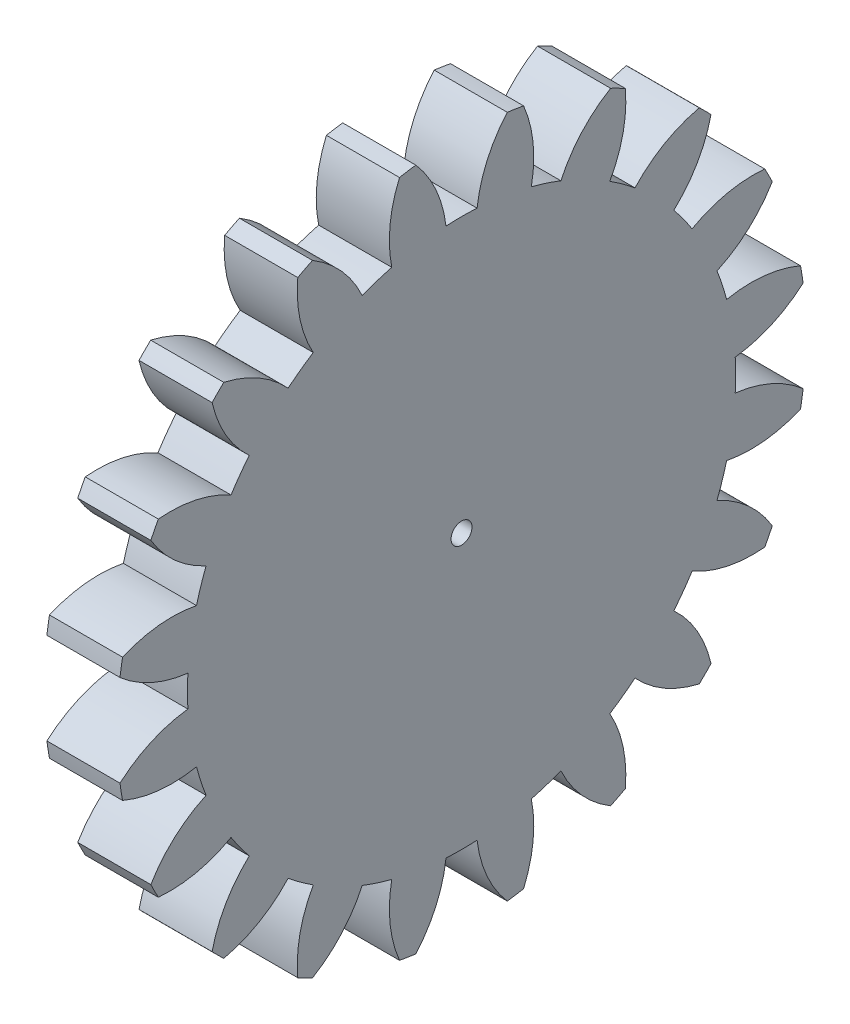
SolidWorks part; units mm, degrees
ref_plane "Plane1" through (0, 0, 0) normal (0, 0, 1) x (1, 0, 0)
ref_plane "Plane2" through (0, 0, 0) normal (0, 1, 0) x (1, 0, 0)
ref_plane "Plane3" through (0, 0, 0) normal (1, 0, 0) x (0, 0, -1)
other "Configuration Table"
sketch "HoldingSke" plane through (0, 0, 0) normal (0, 1, 0) x (1, 0, 0)
  line L0 (0, 0) -> (0.6265, -0.228)
  line L1 (-15, 0) -> (100, 0) construction
  line L2 (0, 0) -> (-2.1039, 2.3779)
  line L3 (0, 0) -> (-11.863, 4.5341)
  line L4 (0, 0) -> (8.1152, 2.9537)
  line L5 (0, 0) -> (-46.8476, -17.4728)
  line L6 (0, 0) -> (-2.9014, -1.9576)
  line L7 (-2.1039, 2.3779) -> (8.6586, 51.2059)
  line L8 (-76.2, 54.61) -> (-76.1, 54.61)
  line L9 (-71.009, 38.7566) -> (-53.1078, 45.2721)
  line L10 (-76.2, 71.12) -> (104.1128, 71.12)
  line L11 (0, 0) -> (-3.5, 0)
  line L12 (-76.2, 101.6) -> (-76.147, 101.6)
  line L13 (24.9733, 27.94) -> (52.9518, 28.4284)
  line L14 (24.9733, 27.94) -> (24.9743, 27.94)
  line L15 (24.9733, 27.94) -> (100.4006, 29.5858)
  line L16 (-63.627, -1.5) -> (-12.827, -1.5)
  circle A0 centre (0, 0) radius 0.5
  circle A1 centre (0, 0) radius 13.124
  circle A2 centre (0, 0) radius 37.5
  circle A3 centre (0, 0) radius 0.5
  dimension "MHD" = 26.248
  dimension "Hub_dia" = 75
  dimension "Bore" = 1
  dimension "MBD" = 1
  dimension "Num_teeth" = 20
  dimension "Pitch" = 0.6667
  dimension "Overall_len" = 50
  dimension "Show_teeth" = 20
  dimension "Thickness" = 3.5
  dimension "OAL" = 50.0001
  dimension "T_dim" = 0.1
  dimension "Ap" = 20
  dimension "H" = 19.05
  dimension "Pitch_radius" = 180.3128
  dimension "Width" = 3.5
  dimension "Backlash" = 0.053
  dimension "Addendum_fac" = 1
  dimension "Dedendum_fac" = 1.25
  dimension "Clearance_fac" = 0.25
  dimension "Dedendum_add" = 0.001
  dimension "Module" = 1.5
sketch "BasProSke" plane through (0, 0, 0) normal (0, 1, 0) x (1, 0, 0)
  line L0 (-10, 0) -> (60, 0) construction
  line L1 (0, 0) -> (0, 16.5)
  line L2 (0, 0) -> (3.5, 0)
  line L3 (3.5, 0) -> (3.5, 16.5)
  line L4 (3.5, 16.5) -> (0, 16.5)
  dimension "Thickness" = 3.5
  dimension "Diameter" = 33
revolve "Base-Revolve" add sketch "BasProSke" angle 360 about L0
sketch "TooCutSke" plane through (0, 0, 0) normal (1, 0, 0) x (0, 0, -1)
  line L1 (0, 0) -> (0, 107) construction
  line L2 (0, 0) -> (-1.2696, 14.9462) construction
  line L3 (0, 0) -> (-4.6808, 29.5532) construction
  line L4 (-1.2696, 14.9462) -> (-2.3404, 14.7766) construction
  arc A0 (0.7438, 13.1029) -> (-0.7438, 13.1029) centre (0, 0) ccw
  arc A1 (2.21, 16.377) -> (-2.21, 16.377) centre (0, 0) ccw
  circle A2 centre (0, 0) radius 15 construction
  circle A3 centre (0, 0) radius 14.0954 construction
  arc A4 (-0.7438, 13.1029) -> (-2.21, 16.377) centre (-6.7025, 12.3999) ccw
  arc A5 (2.21, 16.377) -> (0.7438, 13.1029) centre (6.7025, 12.3999) ccw
  dimension "Root_dia" = 26.248
  dimension "Overcut_dia" = 33.0508
  dimension "Pitch_dia" = 30
  dimension "Base_dia" = 28.1908
  dimension "Flank_rad" = 6
  dimension "Half_ang" = 9
  dimension "Half_CT" = 1.0841
extrude "ToothCut" cut sketch "TooCutSke" along normal through all
fillet "Breaks" [suppressed] radius 0.03
fillet "RootFillets" [suppressed] radius 0.376
pattern_circular "TeethCuts" count 20 every 18 about axis through (-10, 0, 0) along (1, 0, 0) of "ToothCut", "RootFillets", "Breaks"
sketch "HubNeaOneSke" plane through (0, 0, 0) normal (-1, 0, 0) x (0, 0, 1)
  circle A0 centre (0, 0) radius 13.124
  dimension "Diameter" = 26.248
extrude "HubNearOne" [suppressed] add sketch "HubNeaOneSke" along normal blind 46.5001
sketch "HubNeaBotSke" plane through (0, 0, 0) normal (-1, 0, 0) x (0, 0, 1)
  circle A0 centre (0, 0) radius 13.124
  dimension "Diameter" = 26.248
extrude "HubNearBoth" [suppressed] add sketch "HubNeaBotSke" along normal blind 23.25
ref_plane "FarPln" through (3.5, 0, 0) normal (1, 0, 0) x (0, 0, -1)
sketch "HubFarSke" plane through (3.5, 0, 0) normal (1, 0, 0) x (0, 0, -1)
  circle A0 centre (0, 0) radius 13.124
  dimension "Diameter" = 26.248
extrude "HubFar" [suppressed] add sketch "HubFarSke" along normal blind 23.25
sketch "BorSke" plane through (0, 0, 0) normal (1, 0, 0) x (0, 0, -1)
  circle A0 centre (0, 0) radius 0.5
  dimension "Diameter" = 1
extrude "Bore" cut sketch "BorSke" along normal mid plane 100.0001
sketch "KeySke" plane through (0, 0, 0) normal (1, 0, 0) x (0, 0, -1)
  line L0 (-0.05, 0) -> (-0.05, 0.6)
  line L1 (-0.05, 0.6) -> (0.05, 0.6)
  line L2 (0.05, 0.6) -> (0.05, 0)
  line L3 (0, 0) -> (0, 34) construction
  line L4 (-0.05, 0) -> (0.05, 0)
  dimension "Offset" = 0.6
  dimension "Width" = 0.1
extrude "Keyway" [suppressed] cut sketch "KeySke" along normal mid plane 100.0001
pattern_circular "Keyway2" [suppressed] count 2 every 90 about axis through (-10, 0, 0) along (1, 0, 0)
equation "' \"Module@HoldingSke\" = 6.35"
equation "' \"Num_teeth@HoldingSke\" = 12"
equation "' \"Ap@HoldingSke\" =  20"
equation "' \"Ap@HoldingSke\" = 20"
equation "' \"Width@HoldingSke\" = 0.5 * 25.4"
equation "' \"Hub_dia@HoldingSke\"= 1 * 25.4"
equation "' \"Hub_dia@HoldingSke\" = 1 * 25.4"
equation "' \"Overall_len@HoldingSke\" = 1.0 * 25.4"
equation "' \"Bore@HoldingSke\" = 0.75 * 25.4"
equation "' \"T_dim@HoldingSke\" = 0.1 * 25.4"
equation "' \"Width@KeySke\" = 0.25 * 25.4"
equation "' \"Show_teeth@HoldingSke\" = 13"
equation "' \"Backlash@HoldingSke\" = 0.009 * 25.4"
equation "' \"Addendum_fac@HoldingSke\" = 1.0"
equation "' \"Dedendum_fac@HoldingSke\" = 1.25"
equation "' \"Dedendum_add@HoldingSke\" = 0.00005 * 25.4"
equation "' \"Clearance_fac@HoldingSke\" = 0.25"
equation "\"Pitch@HoldingSke\" = 1 / \"Module@HoldingSke\""
equation "\"Overcut_dia@TooCutSke\" = (\"Num_teeth@HoldingSke\" + 2 * \"Addendum_fac@HoldingSke\") / \"Pitch@HoldingSke\" + 0.002 * 25.4"
equation "\"Pitch_dia@TooCutSke\" = \"Num_teeth@HoldingSke\" / \"Pitch@HoldingSke\""
equation "\"Base_dia@TooCutSke\" = \"Num_teeth@HoldingSke\" / \"Pitch@HoldingSke\" * cos((\"Ap@HoldingSke\"  * 3.14159265 / 180))"
equation "\"Root_dia@TooCutSke\" = (\"Num_teeth@HoldingSke\" + 2) / \"Pitch@HoldingSke\" - 2 * (\"Addendum_fac@HoldingSke\" + \"Dedendum_fac@HoldingSke\") / \"Pitch@HoldingSke\" - \"Dedendum_add@HoldingSke\" * 2"
equation "\"Half_ang@TooCutSke\" = 180 / \"Num_teeth@HoldingSke\""
equation "\"Half_CT@TooCutSke\" = \"Num_teeth@HoldingSke\" / \"Pitch@HoldingSke\" * sin((3.14159265 / 2 / \"Num_teeth@HoldingSke\")) / 2 - 7 * \"Backlash@HoldingSke\" / 4"
equation "\"Flank_rad@TooCutSke\" = \"Num_teeth@HoldingSke\" / \"Pitch@HoldingSke\" / 5"
equation "\"Radius@RootFillets\" = \"Clearance_fac@HoldingSke\" / \"Pitch@HoldingSke\" + \"Dedendum_add@HoldingSke\""
equation "\"Break_rad@Breaks\" = 0.02 / \"Pitch@HoldingSke\""
equation "\"Thickness@HoldingSke\" = \"Width@HoldingSke\""
equation "\"OAL@HoldingSke\" = \"Thickness@HoldingSke\""
equation "\"MHD@HoldingSke\" = (\"Num_teeth@HoldingSke\" + 2) / \"Pitch@HoldingSke\" - 2 * (\"Addendum_fac@HoldingSke\" + \"Dedendum_fac@HoldingSke\")  / \"Pitch@HoldingSke\" - \"Dedendum_add@HoldingSke\" * 2"
equation "\"MBD@HoldingSke\" = (\"Num_teeth@HoldingSke\" + 2) / \"Pitch@HoldingSke\" - 2 * (\"Addendum_fac@HoldingSke\" + \"Dedendum_fac@HoldingSke\")  / \"Pitch@HoldingSke\" - \"Dedendum_add@HoldingSke\" * 2 - 0.002 * 25.4"
equation "\"MHD@HoldingSke\" = ((sgn( \"MHD@HoldingSke\" - \"Hub_dia@HoldingSke\" )-1)*( \"MHD@HoldingSke\" - \"Hub_dia@HoldingSke\" ))/-2+ \"Hub_dia@HoldingSke\""
equation "\"MBD@HoldingSke\" = ((sgn( \"MBD@HoldingSke\" - \"Bore@HoldingSke\" )-1)*( \"MBD@HoldingSke\" - \"Bore@HoldingSke\" ))/-2+ \"Bore@HoldingSke\""
equation "\"OAL@HoldingSke\" = ((sgn( \"OAL@HoldingSke\" - \"Overall_len@HoldingSke\" )+1)*( \"OAL@HoldingSke\" - \"Overall_len@HoldingSke\" ))/2 + \"Overall_len@HoldingSke\" + 0.000002 * 25.4"
equation "\"Num_teeth@TeethCuts\" = int( \"Show_teeth@HoldingSke\" ) + 1"
equation "\"Num_teeth@TeethCuts\" = ((sgn( \"Num_teeth@TeethCuts\" - \"Num_teeth@HoldingSke\" )-1)*( \"Num_teeth@TeethCuts\" - \"Num_teeth@HoldingSke\" ))/-2+ \"Num_teeth@HoldingSke\""
equation "\"Num_teeth@TeethCuts\" = ((sgn( \"Num_teeth@TeethCuts\" - 2.0)+1)*( \"Num_teeth@TeethCuts\" - 2.0))/2 +2.0"
equation "\"Angle@TeethCuts\" = 360.0 / \"Num_teeth@HoldingSke\""
equation "\"Diameter@BasProSke\" = (\"Num_teeth@HoldingSke\" + 2 * \"Addendum_fac@HoldingSke\") / \"Pitch@HoldingSke\""
equation "\"Thickness@BasProSke\"  = \"Thickness@HoldingSke\""
equation "' \"Fillet_rad@BasProSke\" =  \"Thickness@HoldingSke\" * 0.05"
equation "' \"Fillet_rad@BasProSke\" = \"Thickness@HoldingSke\" * 0.05"
equation "\"MHD@HoldingSke\" = ((sgn( \"MHD@HoldingSke\" - \"Root_dia@TooCutSke\" )-1)*( \"MHD@HoldingSke\" - \"Root_dia@TooCutSke\" ))/-2+ \"Root_dia@TooCutSke\""
equation "\"Diameter@HubNeaOneSke\" = \"MHD@HoldingSke\""
equation "\"Length@HubNearOne\" = \"OAL@HoldingSke\" - \"Thickness@BasProSke\""
equation "\"Diameter@HubNeaBotSke\" = \"MHD@HoldingSke\""
equation "\"Length@HubNearBoth\" = ( \"OAL@HoldingSke\" - \"Thickness@BasProSke\" ) / 2.0"
equation "\"Thickness@FarPln\" = \"Thickness@BasProSke\""
equation "\"Diameter@HubFarSke\" = \"MHD@HoldingSke\""
equation "\"Length@HubFar\" = ( \"OAL@HoldingSke\" - \"Thickness@BasProSke\" ) / 2.0"
equation "\"Diameter@BorSke\" = \"MBD@HoldingSke\""
equation "\"D1@Bore\" = \"OAL@HoldingSke\" * 2.0"
equation "\"D1@Keyway\" = \"OAL@HoldingSke\" * 2.0"
equation "\"Offset@KeySke\" = \"T_dim@HoldingSke\" + \"MBD@HoldingSke\" / 2.0"
